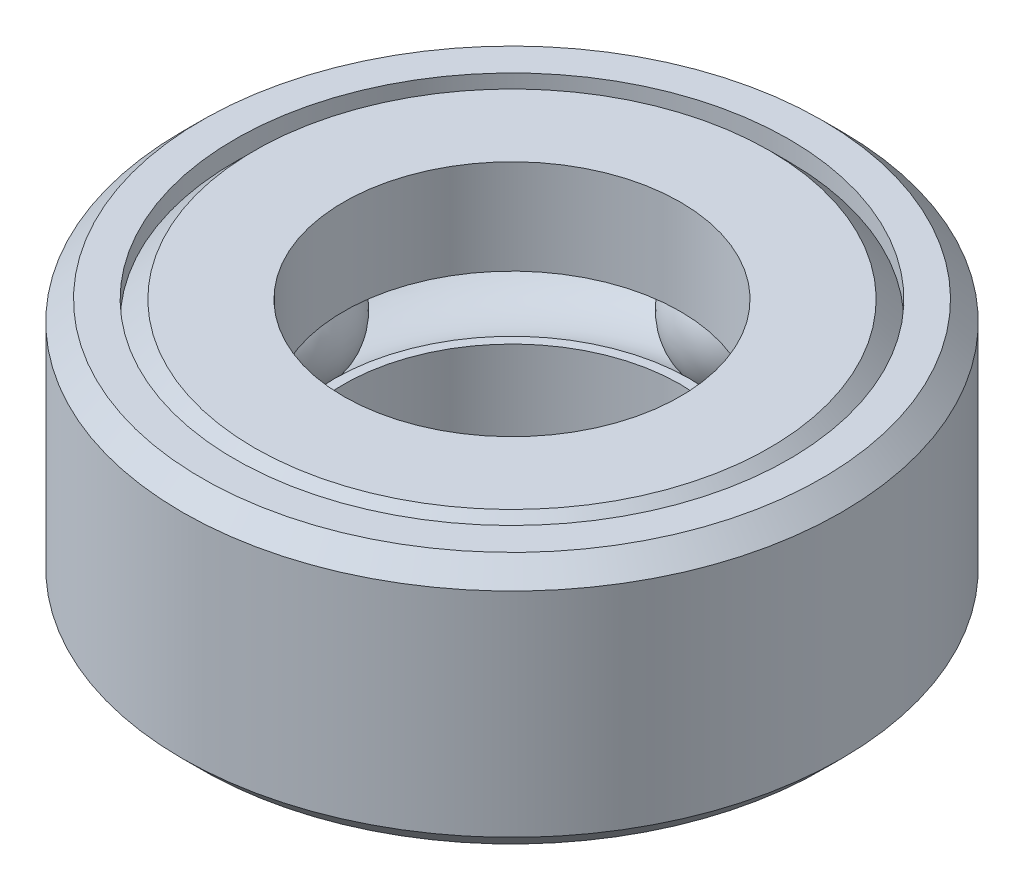
SolidWorks part; units mm, degrees
material "Alloy Steel"
ref_plane "Front Plane" through (0, 0, 0) normal (0, 0, 1) x (1, 0, 0)
ref_plane "Top Plane" through (0, 0, 0) normal (0, 1, 0) x (1, 0, 0)
ref_plane "Right Plane" through (0, 0, 0) normal (1, 0, 0) x (0, 0, -1)
sketch "Sketch1" plane through (0, 0, 0) normal (1, 0, 0) x (0, 0, -1)
  line L0 (18.6531, 0) -> (-18.6531, 0) construction
  line L1 (0, -7.1438) -> (0, 7.1438) construction
  line L2 (-9.525, 1.7859) -> (-9.525, 7.1437) construction
  line L3 (-16.7878, 0) -> (-16.7283, 0) construction
  line L4 (-9.5845, 0) -> (-9.525, 0) construction
  line L5 (-13.1564, 0) -> (-13.1564, 3.5719) construction
  line L6 (-9.525, 1.7859) -> (-10.0631, 1.7859) construction
  line L7 (-16.2497, 1.7859) -> (-16.7878, 1.7859) construction
  line L8 (-16.7878, 1.7859) -> (-16.7878, 4.9245) construction
  line L9 (-16.7878, 4.9245) -> (-14.5685, 7.1437) construction
  line L10 (-14.5685, 7.1437) -> (-9.525, 7.1437) construction
  line L11 (-14.5685, -7.1437) -> (-9.525, -7.1437) construction
  line L12 (-16.7878, -4.9245) -> (-14.5685, -7.1437) construction
  line L13 (-16.7878, -1.7859) -> (-16.7878, -4.9245) construction
  line L14 (-16.2497, -1.7859) -> (-16.7878, -1.7859) construction
  line L15 (-9.525, -1.7859) -> (-10.0631, -1.7859) construction
  line L16 (-9.525, -1.7859) -> (-9.525, -7.1437) construction
  line L17 (-9.525, 7.1437) -> (-9.525, -7.1437)
  line L18 (9.525, 7.1437) -> (9.525, -7.1437)
  line L19 (-14.5685, 7.1437) -> (14.5685, 7.1437) construction
  line L20 (-14.5685, -7.1437) -> (14.5685, -7.1437) construction
  circle A0 centre (-13.1564, 0) radius 3.5719 construction
  point P0 (-9.525, 0)
  point P4 (0, 0)
  point P8 (0, 0)
  point P14 (-16.7878, 0)
  point P18 (-13.1564, 1.7859)
  point P23 (-13.1564, -1.7859)
  point P35 (-9.525, 0)
  dimension "D1" = 7.1437
  dimension "OD" = 37.3062
  dimension "ID" = 19.05
  dimension "D2" = 33.5756
  dimension "D3" = 45
  dimension "Thickness" = 14.2875
sketch "Sketch2" plane through (0, 0, 0) normal (1, 0, 0) x (0, 0, -1)
  line L0 (-16.2497, 1.7859) -> (-16.7878, 1.7859)
  line L1 (-16.7878, 1.7859) -> (-16.7878, 4.9245)
  line L2 (-16.7878, 4.9245) -> (-14.5685, 7.1437)
  line L3 (-14.5685, 7.1437) -> (-9.525, 7.1437)
  line L4 (-9.525, 7.1437) -> (-9.525, 1.7859)
  line L5 (-9.525, 1.7859) -> (-10.0631, 1.7859)
  line L6 (18.6531, 0) -> (-18.6531, 0) construction
  line L7 (18.6531, 0) -> (-18.6531, 0) construction
  line L8 (-9.525, -1.7859) -> (-10.0631, -1.7859)
  line L9 (-9.525, -7.1438) -> (-9.525, -1.7859)
  line L10 (-14.5685, -7.1438) -> (-9.525, -7.1438)
  line L11 (-16.7878, -4.9245) -> (-14.5685, -7.1438)
  line L12 (-16.7878, -1.7859) -> (-16.7878, -4.9245)
  line L13 (-16.2497, -1.7859) -> (-16.7878, -1.7859)
  arc A0 (-16.2497, 1.7859) -> (-10.0631, 1.7859) centre (-13.1564, 0) cw
  circle A1 centre (-13.1564, 0) radius 3.5719 construction
  arc A2 (-16.2497, -1.7859) -> (-10.0631, -1.7859) centre (-13.1564, 0) ccw
revolve "Revolve1" add sketch "Sketch2" angle 360 about L1
sketch "Sketch3" plane through (0, 0, 0) normal (1, 0, 0) x (0, 0, -1)
  line L0 (-15.6782, 6.0341) -> (-15.6782, 7.1437)
  line L1 (-16.7878, 4.9245) -> (-14.5685, 7.1437) construction
  line L2 (-18.6531, 6.0341) -> (-17.5435, 7.1437)
  line L3 (-18.6531, 6.0341) -> (-18.6531, -6.0341)
  line L4 (-17.5435, 7.1437) -> (-15.6782, 7.1437)
  line L5 (-14.5685, 7.1437) -> (-9.525, 7.1437) construction
  line L6 (18.6531, 0) -> (-18.6531, 0) construction
  line L7 (18.6531, 0) -> (-18.6531, 0) construction
  line L8 (-17.5435, -7.1438) -> (-15.6782, -7.1438)
  line L9 (-18.6531, -6.0341) -> (-17.5435, -7.1438)
  line L10 (-15.6782, -6.0341) -> (-15.6782, -7.1438)
  line L11 (-15.6782, 6.0341) -> (-16.7878, 4.9245)
  line L12 (-16.7878, 4.9245) -> (-16.7878, -4.9245)
  line L13 (-16.7878, -4.9245) -> (-15.6782, -6.0341)
revolve "Revolve2" add sketch "Sketch3" angle 360 about L1
sketch "Sketch4" plane through (0, 0, 0) normal (1, 0, 0) x (0, 0, -1)
  line L0 (-13.1564, 3.5719) -> (-13.1564, -3.5719)
  circle A0 centre (-13.1564, 0) radius 3.5719 construction
  arc A1 (-13.1564, -3.5719) -> (-13.1564, 3.5719) centre (-13.1564, 0) ccw
revolve "Revolve3" add sketch "Sketch4" angle 360 about L0
pattern_circular "CirPattern1" count 4 over 360 about axis through (0, 0, 0) along (0, 1, 0) of bodies 107
sketch "Sketch5" plane through (0, 0, 0) normal (1, 0, 0) x (0, 0, -1)
  line L0 (-10.0631, 1.7859) -> (-9.525, 1.7859)
  line L1 (9.525, 1.7859) -> (10.0631, 1.7859)
  line L2 (-9.525, 1.7859) -> (-9.525, 7.1437)
  line L3 (9.525, 7.1437) -> (9.525, 1.7859)
  line L4 (14.5685, 7.1438) -> (9.525, 7.1437)
  line L5 (-9.525, 7.1437) -> (-14.5685, 7.1437)
  line L6 (-14.5685, 7.1437) -> (-16.7878, 4.9245)
  line L7 (16.7878, 4.9245) -> (14.5685, 7.1438)
  line L8 (-16.7878, 4.9245) -> (-16.7878, 1.7859)
  line L9 (16.7878, 1.7859) -> (16.7878, 4.9245)
  line L10 (-16.7878, 1.7859) -> (-16.2497, 1.7859)
  line L11 (16.2497, 1.7859) -> (16.7878, 1.7859)
  line L12 (16.2497, 1.7859) -> (16.7878, 1.7859)
  line L13 (-16.7878, 1.7859) -> (-16.2497, 1.7859)
  line L14 (16.7878, 1.7859) -> (16.7878, 4.9245)
  line L15 (-16.7878, 4.9245) -> (-16.7878, 1.7859)
  line L16 (16.7878, 4.9245) -> (14.5685, 7.1438)
  line L17 (-14.5685, 7.1437) -> (-16.7878, 4.9245)
  line L18 (-9.525, 7.1437) -> (-14.5685, 7.1437)
  line L19 (14.5685, 7.1438) -> (9.525, 7.1437)
  line L20 (9.525, 7.1437) -> (9.525, 1.7859)
  line L21 (-9.525, 1.7859) -> (-9.525, 7.1437)
  line L22 (9.525, 1.7859) -> (10.0631, 1.7859)
  line L23 (-10.0631, 1.7859) -> (-9.525, 1.7859)
  line L24 (10.0631, -1.7859) -> (9.525, -1.7859)
  line L25 (-9.525, -1.7859) -> (-10.0631, -1.7859)
  line L26 (-9.525, -7.1438) -> (-9.525, -1.7859)
  line L27 (9.525, -1.7859) -> (9.525, -7.1438)
  line L28 (-14.5685, -7.1438) -> (-9.525, -7.1438)
  line L29 (9.525, -7.1438) -> (14.5685, -7.1438)
  line L30 (14.5685, -7.1438) -> (16.7878, -4.9245)
  line L31 (-16.7878, -4.9245) -> (-14.5685, -7.1438)
  line L32 (-16.7878, -1.7859) -> (-16.7878, -4.9245)
  line L33 (16.7878, -4.9245) -> (16.7878, -1.7859)
  line L34 (16.7878, -1.7859) -> (16.2497, -1.7859)
  line L35 (-16.2497, -1.7859) -> (-16.7878, -1.7859)
  line L36 (-16.2497, -1.7859) -> (-16.7878, -1.7859)
  line L37 (16.7878, -1.7859) -> (16.2497, -1.7859)
  line L38 (16.7878, -4.9245) -> (16.7878, -1.7859)
  line L39 (-16.7878, -1.7859) -> (-16.7878, -4.9245)
  line L40 (-16.7878, -4.9245) -> (-14.5685, -7.1438)
  line L41 (14.5685, -7.1438) -> (16.7878, -4.9245)
  line L42 (9.525, -7.1438) -> (14.5685, -7.1438)
  line L43 (-14.5685, -7.1438) -> (-9.525, -7.1438)
  line L44 (9.525, -1.7859) -> (9.525, -7.1438)
  line L45 (-9.525, -7.1438) -> (-9.525, -1.7859)
  line L46 (-9.525, -1.7859) -> (-10.0631, -1.7859)
  line L47 (10.0631, -1.7859) -> (9.525, -1.7859)
  line L48 (-16.7878, -4.9245) -> (-16.7878, 4.9245)
  line L49 (16.7878, 4.9245) -> (16.7878, -4.9245)
  line L50 (16.7878, -4.9245) -> (15.6782, -6.0341)
  line L51 (-15.6782, -6.0341) -> (-16.7878, -4.9245)
  line L52 (-12.8207, -7.1438) -> (-15.6782, -6.0341)
  line L53 (15.6782, -6.0341) -> (12.8207, -7.1438)
  line L54 (-14.3685, -7.1438) -> (-12.8207, -7.1438)
  line L55 (12.8207, -7.1438) -> (14.3685, -7.1438)
  line L56 (14.3685, -7.1438) -> (15.4781, -6.0341)
  line L57 (-15.4781, -6.0341) -> (-14.3685, -7.1438)
  line L58 (-15.4781, 6.0341) -> (-15.4781, -6.0341)
  line L59 (15.4781, -6.0341) -> (15.4781, 6.0341)
  line L60 (-14.3685, 7.1438) -> (-15.4781, 6.0341)
  line L61 (15.4781, 6.0341) -> (17.5435, 7.1438)
  line L62 (17.5435, 7.1438) -> (15.6782, 7.1438)
  line L63 (-12.8207, 7.1438) -> (-14.3685, 7.1438)
  line L64 (-15.6782, 6.0341) -> (-12.8207, 7.1438)
  line L65 (15.6782, 7.1438) -> (15.6782, 6.0341)
  line L66 (-16.7878, 4.9245) -> (-15.6782, 6.0341)
  line L67 (15.6782, 6.0341) -> (16.7878, 4.9245)
  line L68 (15.6782, 6.0341) -> (16.7878, 4.9245)
  line L69 (-16.7878, 4.9245) -> (-15.6782, 6.0341)
  line L73 (17.5435, 7.1438) -> (15.6782, 7.1438)
  line L84 (-15.6782, -6.0341) -> (-16.7878, -4.9245)
  line L85 (16.7878, -4.9245) -> (15.6782, -6.0341)
  line L86 (16.7878, 4.9245) -> (16.7878, -4.9245)
  line L87 (-16.7878, -4.9245) -> (-16.7878, 4.9245)
  line L88 (-9.525, 7.1437) -> (9.525, 7.1437)
  line L89 (-9.525, 1.7859) -> (9.525, 1.7859)
  line L90 (9.525, -1.7859) -> (-9.525, -1.7859)
  line L91 (-9.525, -7.1438) -> (9.525, -7.1438)
  arc A0 (-10.0631, 1.7859) -> (-16.2497, 1.7859) centre (-13.1564, 0) ccw
  arc A1 (16.2497, 1.7859) -> (10.0631, 1.7859) centre (13.1564, 0) ccw
  arc A2 (16.2497, 1.7859) -> (10.0631, 1.7859) centre (13.1564, 0) ccw
  arc A3 (-10.0631, 1.7859) -> (-16.2497, 1.7859) centre (-13.1564, 0) ccw
  arc A4 (-16.2497, -1.7859) -> (-10.0631, -1.7859) centre (-13.1564, 0) ccw
  arc A5 (10.0631, -1.7859) -> (16.2497, -1.7859) centre (13.1564, 0) ccw
  arc A6 (10.0631, -1.7859) -> (16.2497, -1.7859) centre (13.1564, 0) ccw
  arc A7 (-16.2497, -1.7859) -> (-10.0631, -1.7859) centre (-13.1564, 0) ccw
  circle A9 centre (13.1564, 0) radius 3.5719
  circle A10 centre (-13.1564, 0) radius 3.5719
  circle A11 centre (-13.1564, 0) radius 3.5719
sketch "Sketch6" plane through (0, 0, 0) normal (0, 1, 0) x (1, 0, 0)
  circle A0 centre (0, 0) radius 18.6531
  circle A1 centre (0, 0) radius 9.525
  dimension "OD Toleranced" = 37.3062
  dimension "For Shaft Diameter for Drawing" = 19.05
equation "\"D1@Sketch1\"=\"Thickness@Sketch1\"/2"
equation "\"D2@Sketch1\"=\"OD@Sketch1\"*.9"
equation "\"D1@CirPattern1\"=\"OD@Sketch1\"*3"
